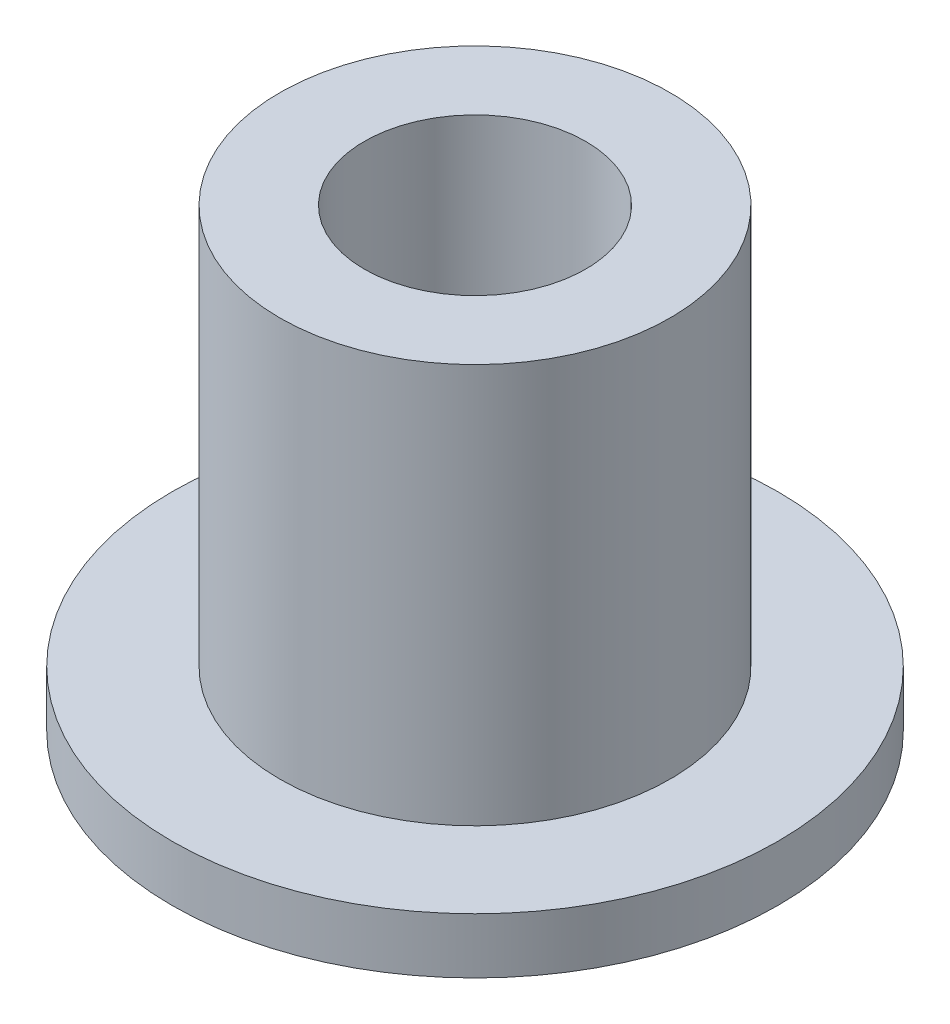
SolidWorks part; units mm, degrees
ref_plane "Front Plane" through (0, 0, 0) normal (0, 0, 1) x (1, 0, 0)
ref_plane "Top Plane" through (0, 0, 0) normal (0, 1, 0) x (1, 0, 0)
ref_plane "Right Plane" through (0, 0, 0) normal (1, 0, 0) x (0, 0, -1)
sketch "Sketch1" plane through (0, 0, 0) normal (0, 0, 1) x (1, 0, 0)
  line L0 (2.19, 0) -> (0, 0) construction
  line L1 (5.99, 0) -> (5.99, 1.1)
  line L2 (5.99, 1.1) -> (3.86, 1.1)
  line L3 (3.86, 1.1) -> (3.86, 9)
  line L4 (3.86, 9) -> (2.19, 9)
  line L5 (2.19, 9) -> (2.19, 0)
  line L6 (2.19, 0) -> (5.99, 0)
  line L7 (0, 0) -> (0, -1.4094) construction
  line L8 (5.99, 0) -> (5.983, -0.0046)
  dimension "D1" = 2.19
  dimension "D2" = 3.8
  dimension "D3" = 1.67
  dimension "D4" = 7.9
  dimension "D5" = 1.1
revolve "Revolve4" add sketch "Sketch1" angle 360 about L7
